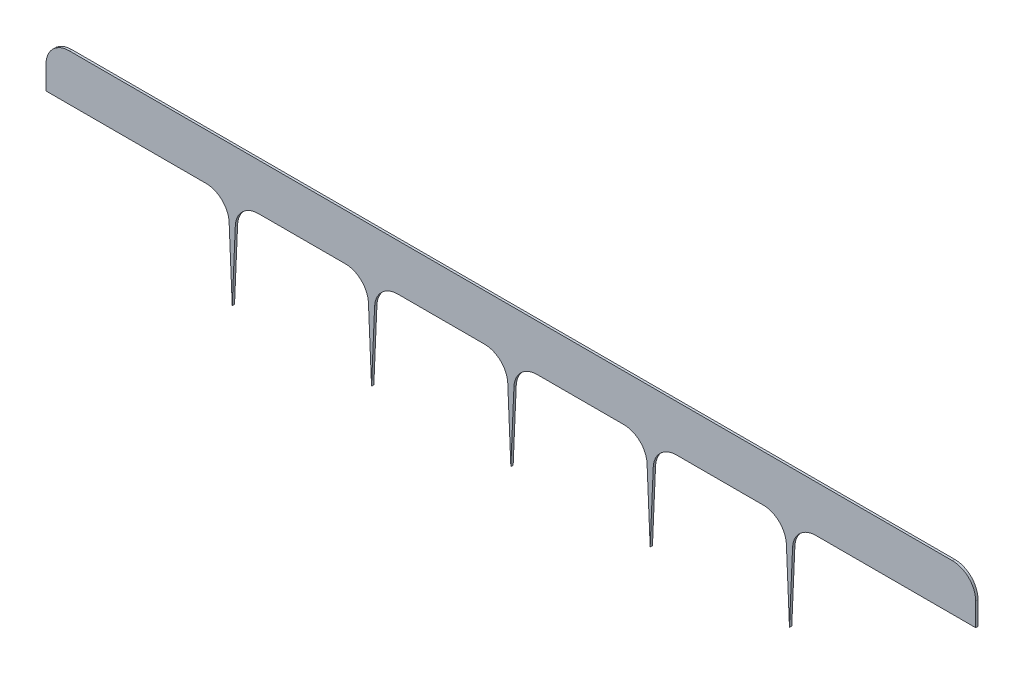
SolidWorks part; units mm, degrees
ref_plane "Front Plane" through (0, 0, 0) normal (0, 0, 1) x (1, 0, 0)
ref_plane "Top Plane" through (0, 0, 0) normal (0, 1, 0) x (1, 0, 0)
ref_plane "Right Plane" through (0, 0, 0) normal (1, 0, 0) x (0, 0, -1)
sketch "Model" plane through (0, 0, 0) normal (0, 0, 1) x (1, 0, 0)
  line L0 (1.9475, 1.5) -> (0.5263, 1.5)
  line L5 (0.7063, 1) -> (1.2483, 1)
  line L7 (0.2763, 1) -> (0.2763, 1.25)
  line L8 (10.2863, 1) -> (10.2863, 1.25)
  line L9 (8.5975, 1.5) -> (10.0363, 1.5)
  line L11 (9.8563, 1) -> (9.3142, 1)
  line L12 (1.2483, 1) -> (1.9983, 1)
  line L13 (8.5975, 1.5) -> (1.9475, 1.5)
  line L14 (2.5642, 1) -> (3.4983, 1)
  line L15 (4.0642, 1) -> (4.9983, 1)
  line L16 (5.5642, 1) -> (6.4983, 1)
  line L17 (7.0642, 1) -> (7.9983, 1)
  line L18 (8.5642, 1) -> (9.3142, 1)
  line L19 (0, 0.1) -> (0.1, 0)
  line L20 (0.1, 0.1) -> (0, 0)
  line L21 (2.248, 0.7609) -> (2.2813, 0)
  line L22 (2.2813, 0) -> (2.3145, 0.7609)
  line L23 (3.748, 0.7609) -> (3.7813, 0)
  line L24 (3.7813, 0) -> (3.8145, 0.7609)
  line L25 (5.248, 0.7609) -> (5.2813, 0)
  line L26 (5.2813, 0) -> (5.3145, 0.7609)
  line L27 (6.748, 0.7609) -> (6.7813, 0)
  line L28 (6.7813, 0) -> (6.8145, 0.7609)
  line L29 (8.248, 0.7609) -> (8.2813, 0)
  line L30 (8.2813, 0) -> (8.3145, 0.7609)
  line L31 (0.7063, 1) -> (0.2763, 1)
  line L32 (9.8563, 1) -> (10.2863, 1)
  arc A0 (0.5263, 1.5) -> (0.2763, 1.25) centre (0.5263, 1.25) ccw
  arc A1 (10.2863, 1.25) -> (10.0363, 1.5) centre (10.0363, 1.25) ccw
  arc A6 (2.248, 0.7609) -> (1.9983, 1) centre (1.9983, 0.75) ccw
  arc A7 (2.5642, 1) -> (2.3145, 0.7609) centre (2.5642, 0.75) ccw
  arc A8 (3.748, 0.7609) -> (3.4983, 1) centre (3.4983, 0.75) ccw
  arc A9 (4.0642, 1) -> (3.8145, 0.7609) centre (4.0642, 0.75) ccw
  arc A10 (5.248, 0.7609) -> (4.9983, 1) centre (4.9983, 0.75) ccw
  arc A11 (5.5642, 1) -> (5.3145, 0.7609) centre (5.5642, 0.75) ccw
  arc A12 (6.748, 0.7609) -> (6.4983, 1) centre (6.4983, 0.75) ccw
  arc A13 (7.0642, 1) -> (6.8145, 0.7609) centre (7.0642, 0.75) ccw
  arc A14 (8.248, 0.7609) -> (7.9983, 1) centre (7.9983, 0.75) ccw
  arc A15 (8.5642, 1) -> (8.3145, 0.7609) centre (8.5642, 0.75) ccw
  point P6 (0.2763, 1.125)
  dimension "D1" = 0.25
  dimension "D2" = 0.25
  dimension "D6" = 0.25
  dimension "D3" = 2.005
  dimension "D4" = 2.005
  dimension "D5" = 5
  dimension "D7" = 1
extrude "Boss-Extrude1" add sketch "Model" along normal blind 0.025
